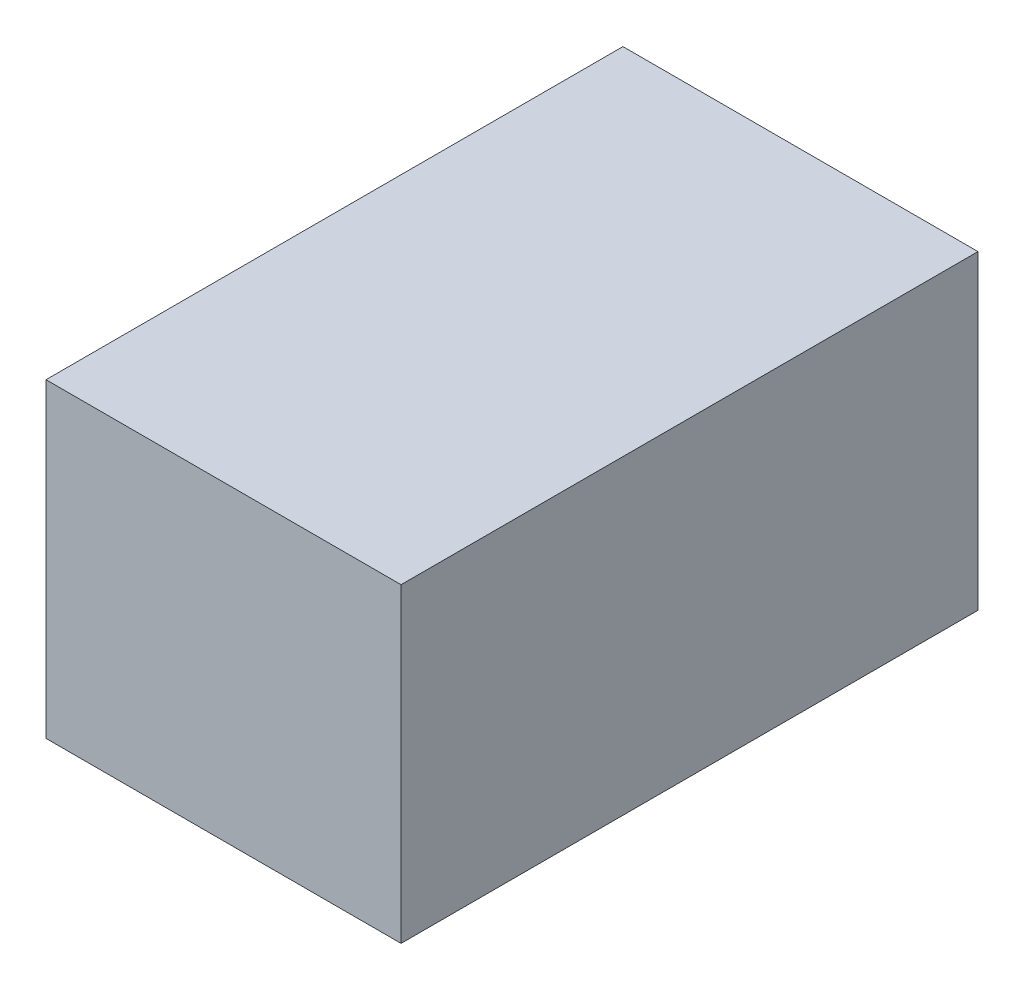
SolidWorks part; units mm, degrees
ref_plane "Front Plane" through (0, 0, 0) normal (0, 0, 1) x (1, 0, 0)
ref_plane "Top Plane" through (0, 0, 0) normal (0, 1, 0) x (1, 0, 0)
ref_plane "Right Plane" through (0, 0, 0) normal (1, 0, 0) x (0, 0, -1)
sketch "Sketch1" plane through (0, 0, 0) normal (1, 0, 0) x (0, 0, -1)
  line L1 (-2300, 1400) -> (300, 1400)
  line L2 (-2300, 1400) -> (-2300, 0)
  line L3 (-2300, 0) -> (300, 0)
  line L4 (300, 1400) -> (300, 0)
  point P4 (0, 0)
  point P5 (0, 0)
  point P6 (0, 0)
extrude "Boss-Extrude1" add sketch "Sketch1" along normal mid plane 1600
